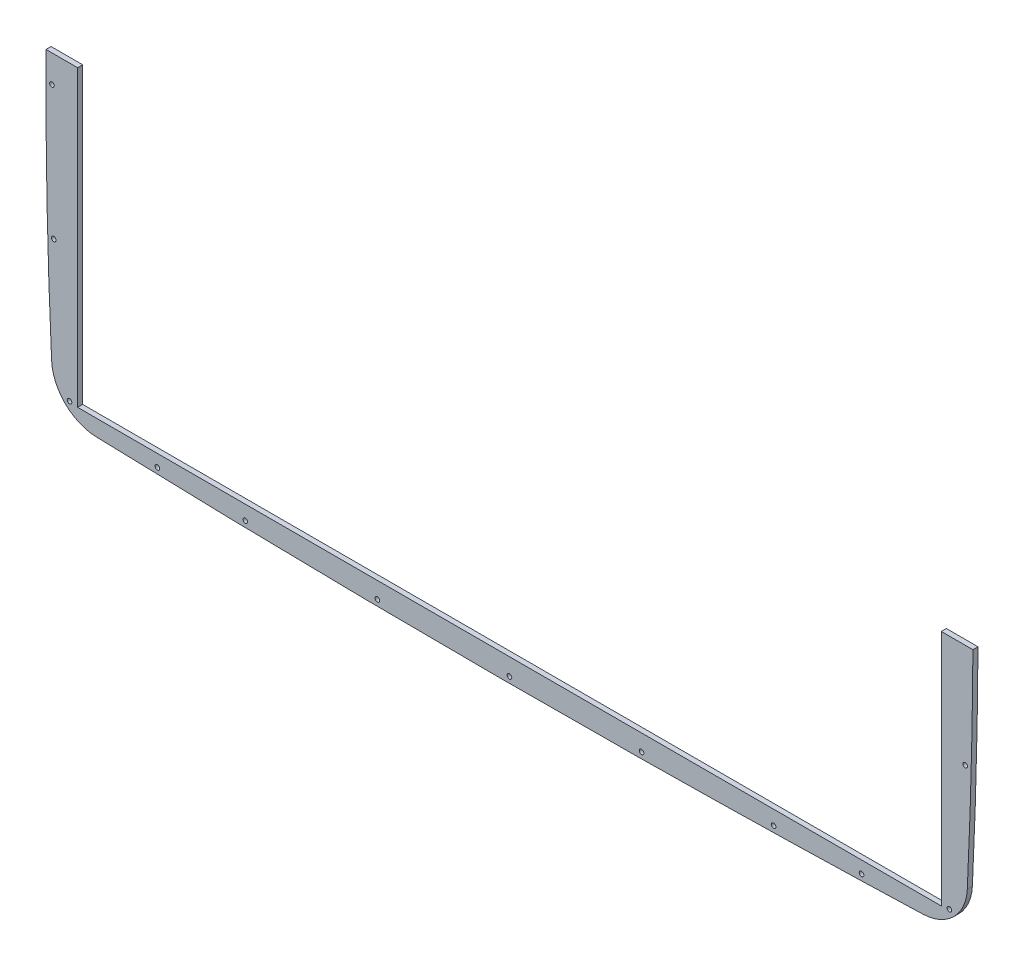
SolidWorks part; units mm, degrees
ref_plane "Front" through (0, 0, 0) normal (0, 0, 1) x (1, 0, 0)
ref_plane "Top" through (0, 0, 0) normal (0, 1, 0) x (1, 0, 0)
ref_plane "Right" through (0, 0, 0) normal (1, 0, 0) x (0, 0, -1)
sketch "Sketch1" plane through (0, 0, 0) normal (0, 0, 1) x (1, 0, 0)
  line L0 (79.622, -180.7786) -> (85.5592, -180.7149)
  line L1 (223.1034, -177.9577) -> (258.4236, -176.8528)
  circle A0 centre (-274.9542, -165.9116) radius 1.435
  arc A93 (-279.7814, -166.2105) -> (-275.1845, -170.7425) centre (-257.4604, -148.1676) ccw
  arc A94 (275.1845, -170.7425) -> (279.7814, -166.2105) centre (257.4604, -148.1676) ccw
  circle A100 centre (-274.9542, 164.9337) radius 1.4351
  circle A101 centre (-284.8103, 82.061) radius 1.4351
  circle A102 centre (-285.9024, 0) radius 1.4351
  circle A103 centre (-284.8103, -83.0389) radius 1.4351
  arc A104 (-258.4236, -176.8528) -> (-223.1034, -177.9577) centre (0, 7519.4009) ccw
  circle A105 centre (-220.0271, -174.2607) radius 1.4351
  circle A106 centre (-165.1, -175.6347) radius 1.4351
  arc A107 (-162.2131, -179.4816) -> (-85.5592, -180.7149) centre (0, 7519.4009) ccw
  arc A108 (-168.1492, -179.3542) -> (-162.2131, -179.4816) centre (0, 7519.4009) ccw
  circle A109 centre (-82.55, -176.963) radius 1.4351
  circle A110 centre (0, -177.4057) radius 1.4351
  circle A111 centre (82.55, -176.963) radius 1.4351
  circle A112 centre (165.1, -175.6347) radius 1.4351
  circle A113 centre (220.0271, -174.2607) radius 1.4351
  circle A114 centre (284.8103, -83.0389) radius 1.4351
  circle A115 centre (285.9024, 0) radius 1.4351
  circle A116 centre (284.8103, 82.061) radius 1.4351
  circle A117 centre (274.9542, 164.9337) radius 1.4351
  circle A118 centre (220.0271, 173.2828) radius 1.4351
  circle A119 centre (165.1, 174.6568) radius 1.4351
  circle A120 centre (82.55, 175.9851) radius 1.4351
  circle A121 centre (0, 176.4278) radius 1.4351
  circle A122 centre (-82.55, 175.9851) radius 1.4351
  circle A123 centre (-220.0271, 173.2828) radius 1.4351
  circle A124 centre (-165.1, 174.6568) radius 1.4351
  arc A125 (-162.2131, 178.5037) -> (-168.1492, 178.3763) centre (0, -7520.3788) ccw
  arc A126 (-85.5592, 179.737) -> (-162.2131, 178.5037) centre (0, -7520.3788) ccw
  arc A127 (-79.622, 179.8007) -> (-85.5592, 179.737) centre (0, -7520.3788) ccw
  arc A128 (-2.9688, 180.2118) -> (-79.622, 179.8007) centre (0, -7520.3788) ccw
  arc A129 (2.9688, 180.2118) -> (-2.9688, 180.2118) centre (0, -7520.3788) ccw
  arc A130 (79.622, 179.8007) -> (2.9688, 180.2118) centre (0, -7520.3788) ccw
  arc A131 (85.5592, 179.737) -> (79.622, 179.8007) centre (0, -7520.3788) ccw
  arc A132 (162.2131, 178.5037) -> (85.5592, 179.737) centre (0, -7520.3788) ccw
  arc A133 (168.1492, 178.3763) -> (162.2131, 178.5037) centre (0, -7520.3788) ccw
  arc A134 (217.1671, 177.1496) -> (168.1492, 178.3763) centre (0, -7520.3788) ccw
  arc A135 (223.1034, 176.9798) -> (217.1671, 177.1496) centre (0, -7520.3788) ccw
  arc A136 (258.4236, 175.8749) -> (223.1034, 176.9798) centre (0, -7520.3788) ccw
  arc A137 (275.1845, 169.7646) -> (258.4236, 175.8749) centre (257.4604, 147.1897) ccw
  arc A138 (279.7814, 165.2326) -> (275.1845, 169.7646) centre (257.4604, 147.1897) ccw
  arc A139 (286.1291, 148.559) -> (279.7814, 165.2326) centre (257.4604, 147.1897) ccw
  arc A140 (288.513, 85.1308) -> (286.1291, 148.559) centre (-2834.64, -0.4889) ccw
  arc A141 (288.6701, 79.1915) -> (288.513, 85.1308) centre (-2834.64, -0.4889) ccw
  arc A142 (289.6845, 2.9713) -> (288.6701, 79.1915) centre (-2834.64, -0.4889) ccw
  arc A143 (289.6854, -2.9701) -> (289.6845, 2.9713) centre (-2834.64, -0.4889) ccw
  arc A144 (288.6701, -80.1694) -> (289.6854, -2.9701) centre (-2834.64, -0.4889) ccw
  arc A145 (288.513, -86.1087) -> (288.6701, -80.1694) centre (-2834.64, -0.4889) ccw
  arc A146 (286.1291, -149.5369) -> (288.513, -86.1087) centre (-2834.64, -0.4889) ccw
  arc A147 (279.7814, -166.2105) -> (286.1291, -149.5369) centre (257.4604, -148.1676) ccw
  arc A148 (275.1845, -170.7425) -> (279.7814, -166.2105) centre (257.4604, -148.1676) ccw
  arc A149 (258.4236, -176.8528) -> (275.1845, -170.7425) centre (257.4604, -148.1676) ccw
  arc A150 (217.1671, -178.1275) -> (223.1034, -177.9577) centre (0, 7519.4009) ccw
  arc A151 (168.1492, -179.3542) -> (217.1671, -178.1275) centre (0, 7519.4009) ccw
  arc A152 (85.5592, -180.7149) -> (162.2131, -179.4816) centre (0, 7519.4009) ccw
  arc A153 (162.2131, -179.4816) -> (168.1492, -179.3542) centre (0, 7519.4009) ccw
  arc A154 (2.9688, -181.1897) -> (79.622, -180.7786) centre (0, 7519.4009) ccw
  arc A155 (-2.9688, -181.1897) -> (2.9688, -181.1897) centre (0, 7519.4009) ccw
  arc A156 (-79.622, -180.7786) -> (-2.9688, -181.1897) centre (0, 7519.4009) ccw
  arc A157 (-85.5592, -180.7149) -> (-79.622, -180.7786) centre (0, 7519.4009) ccw
  arc A158 (-217.1671, -178.1275) -> (-168.1492, -179.3542) centre (0, 7519.4009) ccw
  arc A159 (-223.1034, -177.9577) -> (-217.1671, -178.1275) centre (0, 7519.4009) ccw
  arc A160 (-275.1845, -170.7425) -> (-258.4236, -176.8528) centre (-257.4604, -148.1676) ccw
  arc A161 (-279.7814, -166.2105) -> (-275.1845, -170.7425) centre (-257.4604, -148.1676) ccw
  arc A162 (-286.1291, -149.5369) -> (-279.7814, -166.2105) centre (-257.4604, -148.1676) ccw
  arc A163 (-288.513, -86.1087) -> (-286.1291, -149.5369) centre (2834.64, -0.4889) ccw
  arc A164 (-288.6701, -80.1694) -> (-288.513, -86.1087) centre (2834.64, -0.4889) ccw
  arc A165 (-289.6854, -2.9701) -> (-288.6701, -80.1694) centre (2834.64, -0.4889) ccw
  arc A166 (-289.6845, 2.9713) -> (-289.6854, -2.9701) centre (2834.64, -0.4889) ccw
  arc A167 (-288.6701, 79.1915) -> (-289.6845, 2.9713) centre (2834.64, -0.4889) ccw
  arc A168 (-288.513, 85.1308) -> (-288.6701, 79.1915) centre (2834.64, -0.4889) ccw
  arc A169 (-286.1291, 148.559) -> (-288.513, 85.1308) centre (2834.64, -0.4889) ccw
  arc A170 (-279.7814, 165.2326) -> (-286.1291, 148.559) centre (-257.4604, 147.1897) ccw
  arc A171 (-275.1845, 169.7646) -> (-279.7814, 165.2326) centre (-257.4604, 147.1897) ccw
  arc A172 (-258.4236, 175.8749) -> (-275.1845, 169.7646) centre (-257.4604, 147.1897) ccw
  arc A173 (-223.1034, 176.9798) -> (-258.4236, 175.8749) centre (0, -7520.3788) ccw
  arc A174 (-217.1671, 177.1496) -> (-223.1034, 176.9798) centre (0, -7520.3788) ccw
  arc A175 (-168.1492, 178.3763) -> (-217.1671, 177.1496) centre (0, -7520.3788) ccw
  circle A176 centre (274.9542, -165.9116) radius 1.4351
extrude "Boss-Extrude1" add sketch "Sketch1" along normal blind 3.175
sketch "Sketch2" plane through (0, 0, 0) normal (0, 0, -1) x (-1, 0, 0)
  line L0 (267.0791, 17.1249) -> (305.1791, 17.1249)
  line L1 (267.0791, -157.8028) -> (-267.0791, -157.8028)
  line L2 (267.0791, -157.8028) -> (267.0791, 156.8249)
  line L3 (267.0791, 156.8249) -> (-267.0791, 156.8249)
  line L4 (-267.0791, -157.8028) -> (-267.0791, 156.8249)
  line L5 (-267.0791, -18.1028) -> (-305.1791, -18.1028)
  line L6 (305.1791, 17.1249) -> (305.1791, 212.6886)
  line L7 (305.1791, 212.6886) -> (-305.1791, 212.6886)
  line L8 (-305.1791, 212.6886) -> (-305.1791, -18.1028)
  circle M7 centre (274.9542, 164.9337) radius 1.4351
  circle M8 centre (284.8103, 82.061) radius 1.4351
  circle M19 centre (-285.9024, 0) radius 1.4351
  circle M20 centre (-284.8103, 82.061) radius 1.4351
  circle M21 centre (-274.9542, 164.9337) radius 1.4351
  circle M22 centre (-220.0271, 173.2828) radius 1.4351
  circle M23 centre (-165.1, 174.6568) radius 1.4351
  circle M24 centre (-82.55, 175.9851) radius 1.4351
  circle M25 centre (0, 176.4278) radius 1.4351
  circle M26 centre (82.55, 175.9851) radius 1.4351
  circle M27 centre (220.0271, 173.2828) radius 1.4351
  circle M28 centre (165.1, 174.6568) radius 1.4351
  arc M29 (258.4236, 175.8749) -> (-258.4236, 175.8749) centre (0, -7520.3788) ccw
  arc M30 (-258.4236, 175.8749) -> (-286.1291, 148.559) centre (-257.4604, 147.1897) ccw
  arc M31 (-286.1291, 148.559) -> (-286.1291, -149.5369) centre (2834.64, -0.4889) ccw
  arc M38 (286.1291, -149.5369) -> (286.1291, 148.559) centre (-2834.64, -0.4889) ccw
  arc M39 (286.1291, 148.559) -> (258.4236, 175.8749) centre (257.4604, 147.1897) ccw
  dimension "D1" = 19.05
  dimension "D2" = 19.05
  dimension "D3" = 19.05
  dimension "D4" = 19.05
  dimension "D5" = 38.1
  dimension "D6" = 38.1
  dimension "D7" = 139.7
  dimension "D8" = 139.7
extrude "Cut-Extrude1" cut sketch "Sketch2" against normal through all contours L4 L1 L2 L3 | L5 L4 L3 L2 L0 M38 M39 M29 M30 M31 M8 M20 M22 M24 M26 M28 M27 M25 M23 M21 M19 M7 | L7 L8 L5 L0 L6 M31 M30 M29 M39 M38
sketch "Sketch3" plane through (0, 0, 0) normal (0, 0, -1) x (-1, 0, 0)
  line L0 (269.875, -166.6928) -> (-269.875, -166.6928)
  line L1 (267.0791, -157.8028) -> (-267.0791, -157.8028) construction
  line L2 (267.0791, 17.1249) -> (289.6367, 17.1249) construction
  line L3 (-269.875, -166.6928) -> (269.875, -166.6928)
  line L4 (-269.875, -166.6928) -> (-269.875, 17.1249)
  line L5 (-269.875, 17.1249) -> (269.875, 17.1249)
  line L6 (269.875, -166.6928) -> (269.875, 17.1249)
  point P2 (0, -166.6928)
  point P5 (0, -157.8028)
  line M14 (-267.0791, -18.1028) -> (-289.6367, -18.1028)
  line M23 (289.6367, 17.1249) -> (267.0791, 17.1249)
  line M24 (267.0791, 17.1249) -> (267.0791, -157.8028)
  line M25 (267.0791, -157.8028) -> (-267.0791, -157.8028)
  line M26 (-267.0791, -157.8028) -> (-267.0791, -18.1028)
  dimension "D1" = 539.75
  dimension "D2" = 8.89
extrude "Cut-Extrude2" cut sketch "Sketch3" against normal through all contours L5 L4 M14 M26 M25 M24 | L0 L6 L4 M23 M24 M25 M26 M14
